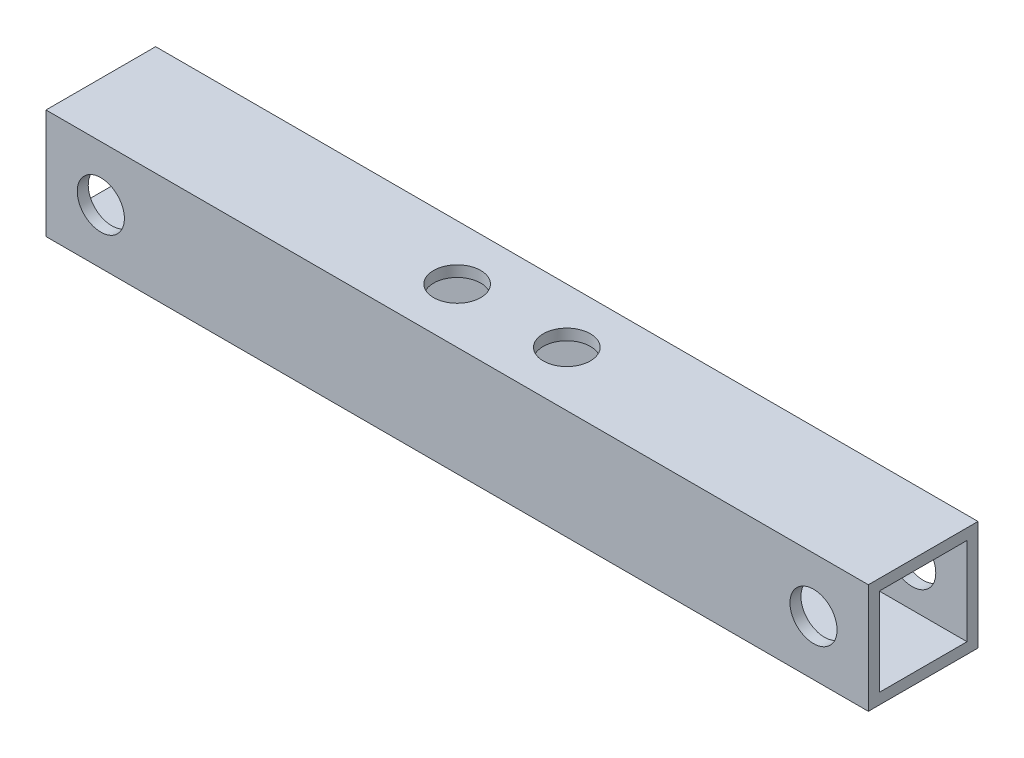
SolidWorks part; units mm, degrees
material "5052-H34"
ref_plane "正面" through (0, 0, 0) normal (0, 0, 1) x (1, 0, 0)
ref_plane "平面" through (0, 0, 0) normal (0, 1, 0) x (1, 0, 0)
ref_plane "右側面" through (0, 0, 0) normal (1, 0, 0) x (0, 0, -1)
sketch "ｽｹｯﾁ1" plane through (0, 0, 0) normal (1, 0, 0) x (0, 0, -1)
  line L1 (-5, 5) -> (5, 5)
  line L2 (-5, 5) -> (-5, -5)
  line L3 (-5, -5) -> (5, -5)
  line L4 (5, 5) -> (5, -5)
  line L5 (-5, 5) -> (5, -5) construction
  line L6 (-5, -5) -> (5, 5) construction
  point P0 (0, 0)
  dimension "D1" = 10
  dimension "D2" = 10
extrude "押し出し-薄板1" add sketch "ｽｹｯﾁ1" along normal blind 75 thin
sketch "ｽｹｯﾁ2" plane through (0, 0, 5) normal (0, 0, 1) x (1, 0, 0)
  line L0 (37.5, 5) -> (37.5, -5) construction
  line L1 (75, 5) -> (0, 5) construction
  line L2 (75, -5) -> (0, -5) construction
  line L3 (75, 0) -> (70, 0) construction
  line L4 (75, 5) -> (75, -5) construction
  circle A0 centre (70, 0) radius 2.15
  circle A1 centre (5, 0) radius 2.15
  dimension "D1" = 4.3
  dimension "D2" = 5
extrude "ｶｯﾄ - 押し出し1" cut sketch "ｽｹｯﾁ2" against normal through all
sketch "ｽｹｯﾁ3" plane through (0, 5, 0) normal (0, 1, 0) x (1, 0, 0)
  line L0 (37.5, 5) -> (37.5, -5) construction
  line L1 (75, 5) -> (0, 5) construction
  line L2 (75, -5) -> (0, -5) construction
  line L3 (37.5, 0) -> (42.5, 0) construction
  circle A0 centre (42.5, 0) radius 2.15
  circle A1 centre (32.5, 0) radius 2.15
  dimension "D1" = 4.3
  dimension "D2" = 10
extrude "ｶｯﾄ - 押し出し2" cut sketch "ｽｹｯﾁ3" against normal through all
